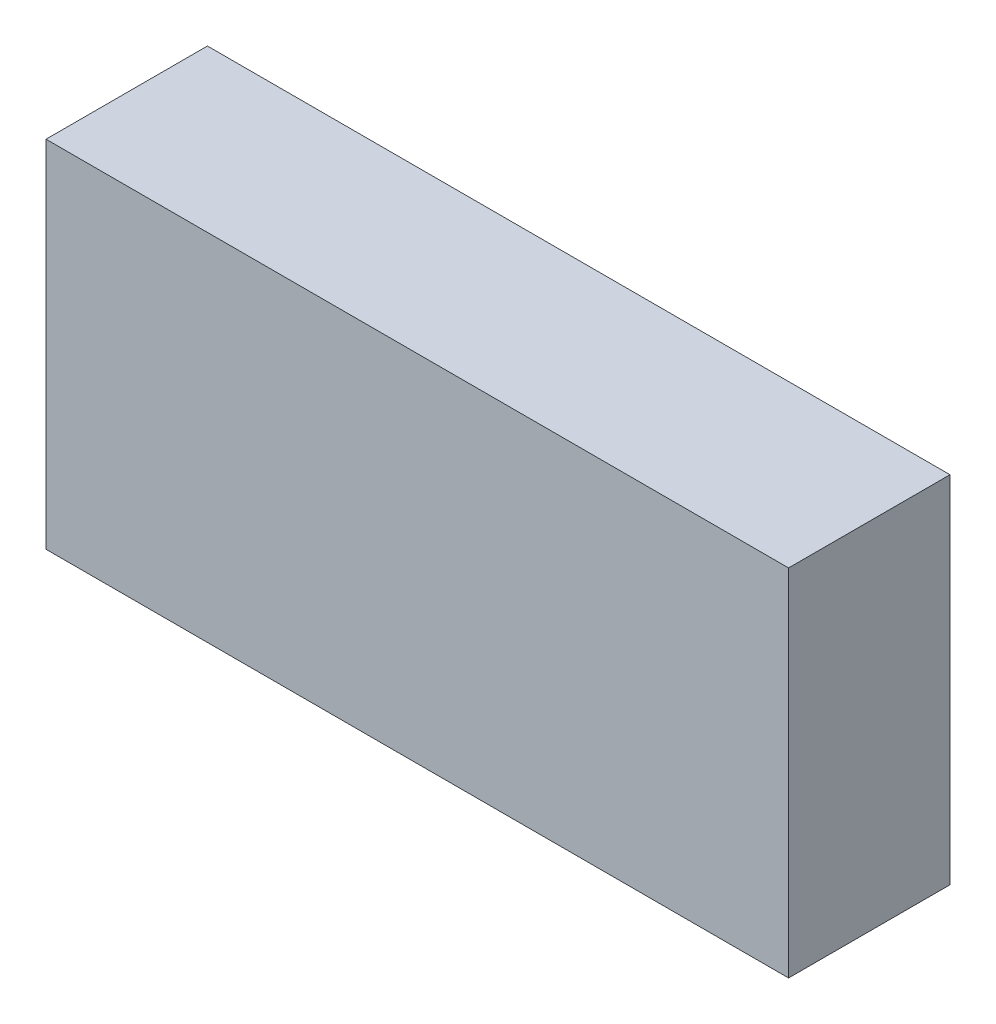
SolidWorks part; units mm, degrees
ref_plane "Front Plane" through (0, 0, 0) normal (0, 0, 1) x (1, 0, 0)
ref_plane "Top Plane" through (0, 0, 0) normal (0, 1, 0) x (1, 0, 0)
ref_plane "Right Plane" through (0, 0, 0) normal (1, 0, 0) x (0, 0, -1)
sketch "Sketch1" plane through (0, 0, 0) normal (0, 1, 0) x (1, 0, 0)
  line L1 (-115, 25) -> (115, 25)
  line L2 (-115, 25) -> (-115, -25)
  line L3 (-115, -25) -> (115, -25)
  line L4 (115, 25) -> (115, -25)
  dimension "D1" = 230
  dimension "D2" = 115
  dimension "D3" = 50
  dimension "D4" = 25
extrude "Boss-Extrude1" add sketch "Sketch1" along normal blind 110
